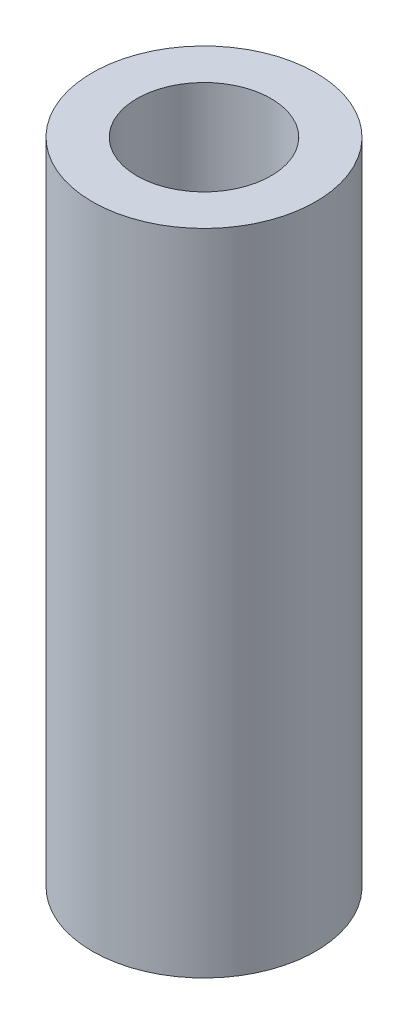
SolidWorks part; units mm, degrees
ref_plane "Front Plane" through (0, 0, 0) normal (0, 0, 1) x (1, 0, 0)
ref_plane "Top Plane" through (0, 0, 0) normal (0, 1, 0) x (1, 0, 0)
ref_plane "Right Plane" through (0, 0, 0) normal (1, 0, 0) x (0, 0, -1)
sketch "Sketch1" plane through (0, 0, 0) normal (0, 1, 0) x (1, 0, 0)
  circle A0 centre (0, 0) radius 5.25
  dimension "D1" = 10.5
extrude "Boss-Extrude1" add sketch "Sketch1" along normal blind 30.5
sketch "Sketch2" plane through (0, 30.5, 0) normal (0, 1, 0) x (1, 0, 0)
  circle A0 centre (0, 0) radius 3.15
  dimension "D1" = 6.3
extrude "Cut-Extrude1" cut sketch "Sketch2" against normal through all
